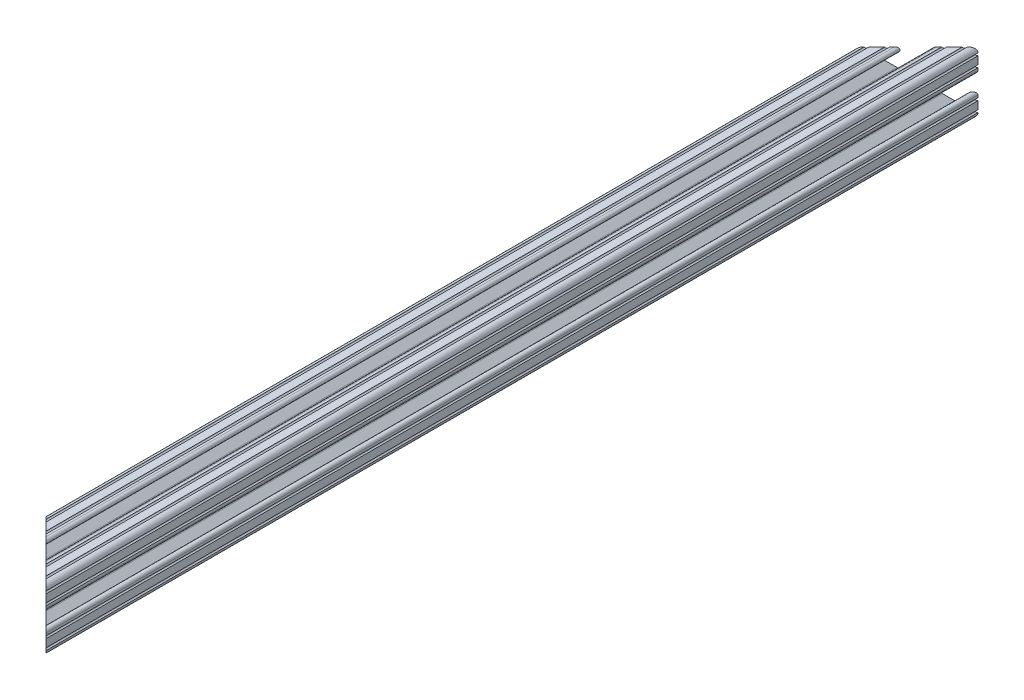
SolidWorks part; units mm, degrees
ref_plane "Front Plane" through (0, 0, 0) normal (0, 0, 1) x (1, 0, 0)
ref_plane "Top Plane" through (0, 0, 0) normal (0, 1, 0) x (1, 0, 0)
ref_plane "Right Plane" through (0, 0, 0) normal (1, 0, 0) x (0, 0, -1)
ref_plane "Plane1" through (0, 0, -101.6) normal (0, 0, -1) x (-1, 0, 0)
sketch "Sketch1" plane through (0, 0, -101.6) normal (0, 0, -1) x (-1, 0, 0)
  line L0 (12.7, -9.5504) -> (12.7, -6.3331)
  line L1 (12.7, -5.3171) -> (12.7, -4.3434)
  line L2 (10.4902, -4.3434) -> (10.4902, -6.4748)
  line L3 (8.7558, -7.1932) -> (5.4257, -3.8632)
  line L4 (4.4958, -1.6181) -> (4.4958, 1.6181)
  line L5 (5.4257, 3.8632) -> (8.7558, 7.1932)
  line L6 (10.4902, 6.4748) -> (10.4902, 4.3434)
  line L7 (12.7, 4.3434) -> (12.7, 5.3171)
  line L8 (12.7, 6.3331) -> (12.7, 9.5504)
  line L9 (9.5504, 12.7) -> (6.3331, 12.7)
  line L10 (5.3171, 12.7) -> (4.3434, 12.7)
  line L11 (4.3434, 10.4902) -> (6.4748, 10.4902)
  line L12 (7.1932, 8.7558) -> (3.8632, 5.4257)
  line L13 (1.6181, 4.4958) -> (-1.6181, 4.4958)
  line L14 (-3.8632, 5.4257) -> (-7.1932, 8.7558)
  line L15 (-6.4748, 10.4902) -> (-4.3434, 10.4902)
  line L16 (-4.3434, 12.7) -> (-5.3171, 12.7)
  line L17 (-6.3331, 12.7) -> (-9.5504, 12.7)
  line L18 (-12.7, 9.5504) -> (-12.7, 6.3331)
  line L19 (-12.7, 5.3171) -> (-12.7, 4.3434)
  line L20 (-10.4902, 4.3434) -> (-10.4902, 6.4748)
  line L21 (-8.7558, 7.1932) -> (-5.4257, 3.8632)
  line L22 (-4.4958, 1.6181) -> (-4.4958, -1.6181)
  line L23 (-5.4257, -3.8632) -> (-8.7558, -7.1932)
  line L24 (-10.4902, -6.4748) -> (-10.4902, -4.3434)
  line L25 (-12.7, -4.3434) -> (-12.7, -5.3171)
  line L26 (-12.7, -6.3331) -> (-12.7, -9.5504)
  line L27 (-9.5504, -12.7) -> (-6.3331, -12.7)
  line L28 (-5.3171, -12.7) -> (-4.3434, -12.7)
  line L29 (-4.3434, -10.4902) -> (-6.4748, -10.4902)
  line L30 (-7.1932, -8.7558) -> (-3.8632, -5.4257)
  line L31 (-1.6181, -4.4958) -> (1.6181, -4.4958)
  line L32 (3.8632, -5.4257) -> (7.1932, -8.7558)
  line L33 (6.4748, -10.4902) -> (4.3434, -10.4902)
  line L34 (4.3434, -12.7) -> (5.3171, -12.7)
  line L35 (6.3331, -12.7) -> (9.5504, -12.7)
  arc A0 (12.6998, -10.5664) -> (12.7, -9.5504) centre (12.7, -10.0584) cw
  arc A1 (12.7, -6.3331) -> (12.7, -5.3171) centre (12.7, -5.8251) cw
  arc A2 (12.7, -4.3434) -> (10.4902, -4.3434) centre (11.5951, -4.3434) ccw
  arc A3 (10.4902, -6.4748) -> (8.7558, -7.1932) centre (9.4742, -6.4748) cw
  arc A4 (5.4257, -3.8632) -> (4.4958, -1.6181) centre (7.6708, -1.6181) cw
  arc A5 (4.4958, 1.6181) -> (5.4257, 3.8632) centre (7.6708, 1.6181) cw
  arc A6 (8.7558, 7.1932) -> (10.4902, 6.4748) centre (9.4742, 6.4748) cw
  arc A7 (10.4902, 4.3434) -> (12.7, 4.3434) centre (11.5951, 4.3434) ccw
  arc A8 (12.7, 5.3171) -> (12.7, 6.3331) centre (12.7, 5.8251) cw
  arc A9 (12.7, 9.5504) -> (12.6998, 10.5664) centre (12.7, 10.0584) cw
  arc A10 (12.6998, 10.5664) -> (10.5664, 12.6998) centre (10.5918, 10.5918) ccw
  arc A11 (10.5664, 12.6998) -> (9.5504, 12.7) centre (10.0584, 12.7) cw
  arc A12 (6.3331, 12.7) -> (5.3171, 12.7) centre (5.8251, 12.7) cw
  arc A13 (4.3434, 12.7) -> (4.3434, 10.4902) centre (4.3434, 11.5951) ccw
  arc A14 (6.4748, 10.4902) -> (7.1932, 8.7558) centre (6.4748, 9.4742) cw
  arc A15 (3.8632, 5.4257) -> (1.6181, 4.4958) centre (1.6181, 7.6708) cw
  arc A16 (-1.6181, 4.4958) -> (-3.8632, 5.4257) centre (-1.6181, 7.6708) cw
  arc A17 (-7.1932, 8.7558) -> (-6.4748, 10.4902) centre (-6.4748, 9.4742) cw
  arc A18 (-4.3434, 10.4902) -> (-4.3434, 12.7) centre (-4.3434, 11.5951) ccw
  arc A19 (-5.3171, 12.7) -> (-6.3331, 12.7) centre (-5.8251, 12.7) cw
  arc A20 (-9.5504, 12.7) -> (-10.5664, 12.6998) centre (-10.0584, 12.7) cw
  arc A21 (-10.5664, 12.6998) -> (-12.6998, 10.5664) centre (-10.5918, 10.5918) ccw
  arc A22 (-12.6998, 10.5664) -> (-12.7, 9.5504) centre (-12.7, 10.0584) cw
  arc A23 (-12.7, 6.3331) -> (-12.7, 5.3171) centre (-12.7, 5.8251) cw
  arc A24 (-12.7, 4.3434) -> (-10.4902, 4.3434) centre (-11.5951, 4.3434) ccw
  arc A25 (-10.4902, 6.4748) -> (-8.7558, 7.1932) centre (-9.4742, 6.4748) cw
  arc A26 (-5.4257, 3.8632) -> (-4.4958, 1.6181) centre (-7.6708, 1.6181) cw
  arc A27 (-4.4958, -1.6181) -> (-5.4257, -3.8632) centre (-7.6708, -1.6181) cw
  arc A28 (-8.7558, -7.1932) -> (-10.4902, -6.4748) centre (-9.4742, -6.4748) cw
  arc A29 (-10.4902, -4.3434) -> (-12.7, -4.3434) centre (-11.5951, -4.3434) ccw
  arc A30 (-12.7, -5.3171) -> (-12.7, -6.3331) centre (-12.7, -5.8251) cw
  arc A31 (-12.7, -9.5504) -> (-12.6998, -10.5664) centre (-12.7, -10.0584) cw
  arc A32 (-12.6998, -10.5664) -> (-10.5664, -12.6998) centre (-10.5918, -10.5918) ccw
  arc A33 (-10.5664, -12.6998) -> (-9.5504, -12.7) centre (-10.0584, -12.7) cw
  arc A34 (-6.3331, -12.7) -> (-5.3171, -12.7) centre (-5.8251, -12.7) cw
  arc A35 (-4.3434, -12.7) -> (-4.3434, -10.4902) centre (-4.3434, -11.5951) ccw
  arc A36 (-6.4748, -10.4902) -> (-7.1932, -8.7558) centre (-6.4748, -9.4742) cw
  arc A37 (-3.8632, -5.4257) -> (-1.6181, -4.4958) centre (-1.6181, -7.6708) cw
  arc A38 (1.6181, -4.4958) -> (3.8632, -5.4257) centre (1.6181, -7.6708) cw
  arc A39 (7.1932, -8.7558) -> (6.4748, -10.4902) centre (6.4748, -9.4742) cw
  arc A40 (4.3434, -10.4902) -> (4.3434, -12.7) centre (4.3434, -11.5951) ccw
  arc A41 (5.3171, -12.7) -> (6.3331, -12.7) centre (5.8251, -12.7) cw
  arc A42 (9.5504, -12.7) -> (10.5664, -12.6998) centre (10.0584, -12.7) cw
  arc A43 (10.5664, -12.6998) -> (12.6998, -10.5664) centre (10.5918, -10.5918) ccw
  circle A44 centre (0, 0) radius 2.6035
extrude "Boss-Extrude1" add sketch "Sketch1" against normal blind 381
sketch "Sketch2" plane through (0, 0, 0) normal (0, 1, 0) x (1, 0, 0)
  line L0 (12.7, 101.6) -> (-12.7, 101.6)
  line L6 (-12.7, 101.6) -> (-12.7, 76.2)
  line L7 (-12.7, -279.4) -> (-12.7, 101.6) construction
  line L8 (-12.7, 76.2) -> (12.7, 101.6)
  dimension "D1" = 45
extrude "Cut-Extrude2" cut sketch "Sketch2" against normal through all both and the other way through all
sketch "Sketch4" plane through (0, 0, 0) normal (0, 1, 0) x (1, 0, 0)
  line L0 (-12.7, -279.4) -> (12.7, -279.4)
  line L1 (12.7, -279.4) -> (-12.7, -254)
  line L2 (-12.7, -279.4) -> (-12.7, 76.2) construction
  line L3 (-12.7, -254) -> (-12.7, -279.4)
  dimension "D1" = 45
extrude "Cut-Extrude3" cut sketch "Sketch4" against normal through all both and the other way through all
